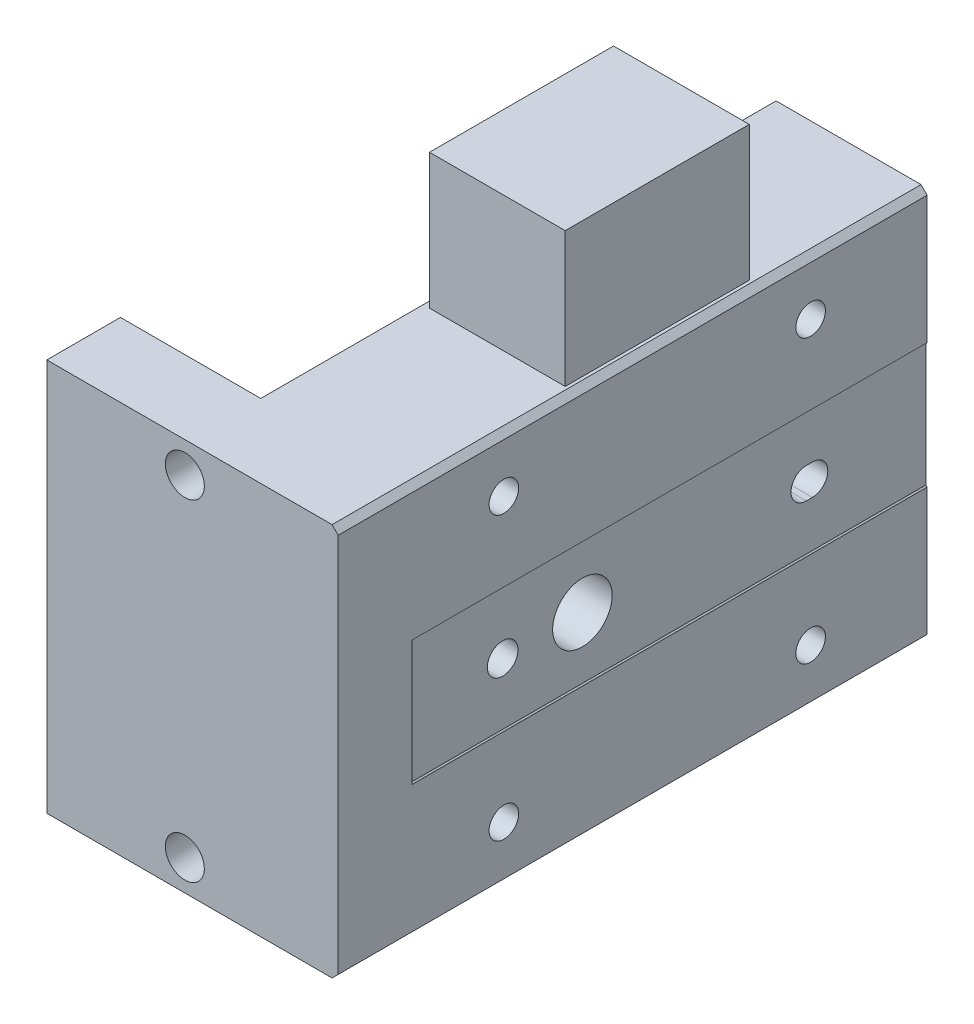
SolidWorks part; units mm, degrees
ref_plane "Front" through (0, 0, 0) normal (0, 0, 1) x (1, 0, 0)
ref_plane "Top" through (0, 0, 0) normal (0, 1, 0) x (1, 0, 0)
ref_plane "Right" through (0, 0, 0) normal (1, 0, 0) x (0, 0, -1)
sketch "Sketch1" plane through (0, 0, -1312.7398) normal (0, 0, 1) x (1, 0, 0)
  line L0 (12.0523, 32) -> (-12.0523, 32) construction
  line L1 (-10.1873, 32) -> (37.3127, 32)
  line L2 (-10.1873, 32) -> (-10.1873, -32)
  line L3 (-10.1873, -32) -> (37.3127, -32)
  line L4 (37.3127, 32) -> (37.3127, 10.2)
  line L5 (-10.1873, 0) -> (37.1127, 0) construction
  line L6 (-12.6873, 31.365) -> (-12.6873, 9.271) construction
  line L8 (-3.6957, -32) -> (3.6957, -32) construction
  line L9 (37.1127, 10) -> (37.1127, -10)
  line L10 (37.1127, -10) -> (37.3127, -10.2)
  line L11 (37.1127, 10) -> (37.3127, 10.2)
  line L12 (37.3127, -10.2) -> (37.3127, -32)
  dimension "D1" = 2.5
  dimension "D2" = 50
  dimension "D3" = 45
  dimension "D4" = 0.2
  dimension "D5" = 20
extrude "Base-Extrude" add sketch "Sketch1" against normal up to surface (12 mm away)
sketch "Sketch3" plane through (0, 0, -1312.7398) normal (0, 0, -1) x (-1, 0, 0)
  line L0 (-37.3127, 10.2) -> (-37.3127, 32) construction
  line L1 (-37.3127, 32) -> (10.1873, 32) construction
  line L2 (-37.3127, 10.2) -> (-37.3127, 32)
  line L3 (-37.3127, 32) -> (-12.6873, 32)
  line L4 (10.1873, -32) -> (-37.3127, -32) construction
  line L5 (-37.3127, -32) -> (-37.3127, -10.2) construction
  line L6 (-37.3127, -10.2) -> (-37.1127, -10) construction
  line L7 (-37.1127, -10) -> (-37.1127, 10) construction
  line L8 (-37.1127, 10) -> (-37.3127, 10.2) construction
  line L9 (-12.6873, -32) -> (-37.3127, -32)
  line L10 (-37.3127, -32) -> (-37.3127, -10.2)
  line L11 (-37.3127, -10.2) -> (-37.1127, -10)
  line L12 (-37.1127, -10) -> (-37.1127, 10)
  line L13 (-37.1127, 10) -> (-37.3127, 10.2)
  line L14 (-12.6873, -9.271) -> (-12.6873, -31.365) construction
  line L19 (-12.6873, 32) -> (-12.6873, -32)
extrude "Boss-Extrude1" add sketch "Sketch3" along normal up to surface (84 mm away)
sketch "Sketch15" plane through (0, 0, -1300.7398) normal (0, 0, 1) x (1, 0, 0)
  line L0 (37.1127, -10) -> (37.1127, 10) construction
  line L1 (37.1127, -10) -> (37.1127, 10)
  line L2 (37.3127, -10.2) -> (37.1127, -10) construction
  line L3 (37.3127, -10.2) -> (37.1127, -10)
  line L4 (37.1127, 10) -> (37.3127, 10.2) construction
  line L5 (37.1127, 10) -> (37.3127, 10.2)
  line L6 (37.3127, 10.2) -> (37.3127, -10.2)
extrude "Boss-Extrude3" add sketch "Sketch15" against normal up to surface (12 mm away) up to face at (1.25, -8, -1312.7398)
hole_wizard "9.7 Diameter Hole1" positions "Sketch5" profile "Sketch4" hole size "M9.7" standard "Ansi Metric" end condition through all
sketch "Sketch5" plane through (37.1127, 0, 0) normal (1, 0, 0) x (0, 0, -1)
  point P0 (1340.7398, 0)
sketch "Sketch4" plane through (37.1127, 0, -1340.7398) normal (0, 1, 0) x (0, 0, -1)
  line L0 (0, 0) -> (0, 47.3)
  line L1 (0, 47.3) -> (4.85, 47.3)
  line L2 (4.85, 47.3) -> (4.85, 0)
  line L5 (4.85, 0) -> (0, 0)
  line L11 (0, -6.35) -> (0, 107.95) construction
  dimension "Thru Hole Dia." = 9.7
  dimension "Thru Hole Depth" = 47.3
hole_wizard "#10-32 Tapped Hole1" positions "Sketch7" profile "Sketch6" tap size "#10-32" standard "Ansi Inch"
sketch "Sketch7" plane through (37.3127, 0, 0) normal (1, 0, 0) x (0, 0, -1)
  point P0 (1327.7398, 23)
  point P1 (1377.7398, 23)
  point P3 (1327.7398, -23)
  point P4 (1377.7398, -23)
sketch "Sketch6" plane through (37.3127, 23, -1327.7398) normal (0, 1, 0) x (0, 0, -1)
  line L0 (0, 0) -> (0, 14.0757)
  line L1 (0, 14.0757) -> (2.0193, 12.8624)
  line L2 (2.0193, 12.8624) -> (2.0193, 8.9)
  line L3 (2.0193, 8.9) -> (2.413, 8.9)
  line L4 (2.413, 8.9) -> (2.413, 0)
  line L5 (2.413, 0) -> (0, 0)
  line L10 (0, 14.0757) -> (-2.0193, 12.8624) construction
  line L11 (0, -6.35) -> (0, 107.95) construction
  dimension "Tap Drill Dia." = 4.0386
  dimension "Tap Drill Depth" = 12.8624
  dimension "Thread Dia." = 4.826
  dimension "Thread Depth" = 8.9
  dimension "Drill Angle" = 118
hole_wizard "1/4-20 Tapped Hole1" positions "Sketch10" profile "Sketch9" tap size "1/4-20" standard "Ansi Inch"
sketch "Sketch10" plane through (0, 0, -1300.7398) normal (0, 0, 1) x (1, 0, 0)
  line L0 (-12.6873, 31.365) -> (-12.6873, 9.271) construction
  line L1 (-12.0523, 0) -> (12.3127, 0) construction
  line L2 (-12.0523, 8.636) -> (-12.0523, -8.636) construction
  point P0 (12.3127, 27)
  point P1 (12.3127, -27)
  dimension "D1" = 25
  dimension "D2" = 54
sketch "Sketch9" plane through (12.3127, 27, -1300.7398) normal (1, 0, 0) x (0, -1, 0)
  line L0 (0, 0) -> (0, 12)
  line L1 (0, 12) -> (3.175, 12)
  line L2 (3.175, 12) -> (3.175, 0)
  line L5 (3.175, 0) -> (0, 0)
  line L11 (0, -6.35) -> (0, 107.95) construction
  dimension "Thru Hole Dia." = 6.35
  dimension "Thru Hole Depth" = 12
sketch "Sketch11" plane through (37.1127, 0, 0) normal (1, 0, 0) x (0, 0, -1)
  line L0 (1377.7398, 23) -> (1377.7398, 0) construction
  line L2 (1300.7398, 0) -> (1396.7398, 0) construction
  line L4 (1380.7398, 0) -> (1380.7398, 23) construction
  line L5 (1374.7398, 0) -> (1374.7398, 23) construction
  line L6 (1377.2398, 2.5) -> (1378.2398, 2.5)
  line L7 (1377.2398, -2.5) -> (1378.2398, -2.5)
  arc A0 (1378.2398, -2.5) -> (1378.2398, 2.5) centre (1378.2398, 0) ccw
  arc A1 (1377.2398, 2.5) -> (1377.2398, -2.5) centre (1377.2398, 0) ccw
  dimension "D1" = 5
  dimension "D2" = 6
extrude "Cut-Extrude1" cut sketch "Sketch11" against normal blind 5
hole_wizard "Hole1" positions "Sketch13" profile "Sketch12" legacy
sketch "Sketch13" plane through (37.1127, 0, 0) normal (1, 0, 0) x (0, 0, -1)
  line L0 (1300.7398, 0) -> (1396.7398, 0) construction
  point P0 (1327.7398, 0)
sketch "Sketch12" plane through (37.1127, 0, -1327.7398) normal (0, 1, 0) x (0, 0, -1)
  line L0 (0, 0) -> (0, 5)
  line L1 (0, 5) -> (2.5, 5)
  line L2 (2.5, 5) -> (2.5, 0)
  line L3 (2.5, 0) -> (0, 0)
  line L4 (0, 110) -> (0, -10) construction
  dimension "Diameter" = 5
  dimension "Depth" = 5
sketch "Sketch2" plane through (0, 0, -1300.7398) normal (0, 0, 1) x (1, 0, 0)
  line L0 (37.3127, -32) -> (37.3127, 32) construction
  line L3 (37.3127, -32) -> (37.3127, 32) construction
  circle A0 centre (29.3127, 17.5) radius 3
  circle A2 centre (0, 14.9352) radius 4
  circle A3 centre (0, -16.4592) radius 4
  circle A4 centre (22.3127, 26) radius 3
  circle A5 centre (22.3127, -26) radius 3
  circle A6 centre (29.3127, -17.5) radius 3
  dimension "D1" = 6
  dimension "D4" = 8
  dimension "D2" = 8
  dimension "D3" = 15
sketch "Sketch14" plane through (0, 32, 0) normal (0, 1, 0) x (-1, 0, 0)
  line L1 (-35.8127, -1339.2398) -> (-13.6873, -1339.2398)
  line L2 (-35.8127, -1339.2398) -> (-35.8127, -1369.2398)
  line L3 (-35.8127, -1369.2398) -> (-13.6873, -1369.2398)
  line L4 (-13.6873, -1339.2398) -> (-13.6873, -1369.2398)
  line L5 (-37.3127, -1300.7398) -> (-37.3127, -1396.7398) construction
  line L6 (-12.6873, -1396.7398) -> (-12.6873, -1312.7398) construction
  line L7 (-8.925, -1339.2398) -> (8.925, -1339.2398) construction
  dimension "D1" = 30
  dimension "D3" = 1.5
  dimension "D4" = 1
extrude "Boss-Extrude2" add sketch "Sketch14" along normal blind 22
chamfer "Chamfer1" distance 1 angle 45 2 edges at (37.3127, 32, -1348.7398) (37.3127, -32, -1348.7398)
